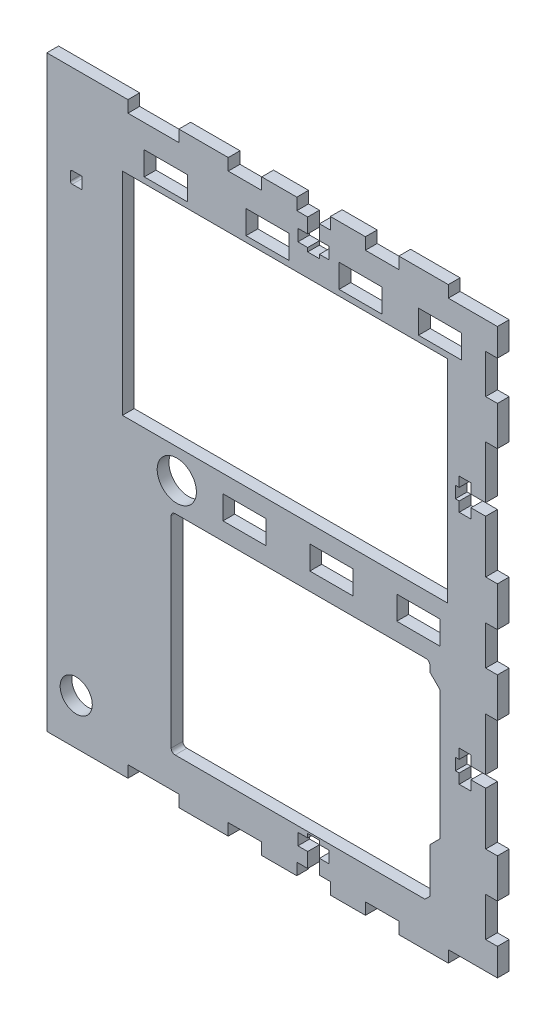
SolidWorks part; units mm, degrees
material "Balsa"
ref_plane "Alzado" through (0, 0, 0) normal (0, 0, 1) x (1, 0, 0)
ref_plane "Planta" through (0, 0, 0) normal (0, 1, 0) x (1, 0, 0)
ref_plane "Vista lateral" through (0, 0, 0) normal (1, 0, 0) x (0, 0, -1)
sketch "Croquis1" plane through (0, 0, 0) normal (0, 0, 1) x (1, 0, 0)
  line L0 (-0.0001, 147) -> (-0.0001, 1.377)
  line L1 (99.9999, 2.9999) -> (99.9999, 9.9999)
  line L2 (99.9999, 9.9999) -> (96.9999, 9.9999)
  line L3 (96.9999, 9.9999) -> (96.9999, 19.9999)
  line L4 (96.9999, 19.9999) -> (99.9999, 19.9999)
  line L5 (99.9999, 19.9999) -> (99.9999, 29.9999)
  line L6 (99.9999, 69.9999) -> (96.9999, 69.9999)
  line L7 (96.9999, 69.9999) -> (96.9999, 79.9999)
  line L8 (96.9999, 79.9999) -> (99.9999, 79.9999)
  line L9 (99.9999, 119.9999) -> (99.9999, 129.9999)
  line L10 (99.9999, 129.9999) -> (96.9999, 129.9999)
  line L11 (96.9999, 129.9999) -> (96.9999, 139.9999)
  line L12 (96.9999, 139.9999) -> (99.9999, 139.9999)
  line L13 (99.9999, 147) -> (99.9999, 139.9999)
  line L14 (96.9999, 46.4372) -> (96.9999, 59.8749)
  line L15 (96.9999, 106.5622) -> (96.9999, 119.9999)
  line L17 (63.1318, 69.011) -> (52.1318, 69.011)
  line L22 (4.2999, 79.511) -> (87.2999, 79.511)
  line L23 (87.2999, 79.511) -> (87.2999, 133.511)
  line L24 (87.2999, 133.511) -> (4.2999, 133.511)
  line L25 (4.2999, 133.511) -> (4.2999, 79.511)
  line L26 (82.7746, 61.971) -> (82.7746, 63.495)
  line L27 (81.7586, 64.511) -> (17.7506, 64.511)
  line L28 (16.7346, 63.495) -> (16.7346, 12.187)
  line L29 (17.7506, 11.171) -> (81.5046, 11.171)
  line L30 (81.5046, 11.171) -> (82.7746, 12.441)
  line L31 (82.7746, 12.441) -> (82.7746, 23.871)
  line L32 (82.7746, 23.871) -> (85.3146, 26.411)
  line L33 (85.3146, 26.411) -> (85.3146, 59.431)
  line L34 (85.3146, 59.431) -> (82.7746, 61.971)
  line L35 (63.1318, 69.011) -> (63.1318, 75.011)
  line L36 (63.1318, 75.011) -> (52.1318, 75.011)
  line L37 (52.1318, 69.011) -> (52.1318, 75.011)
  line L38 (40.9518, 69.011) -> (29.9518, 69.011)
  line L39 (40.9518, 69.011) -> (40.9518, 75.011)
  line L40 (40.9518, 75.011) -> (29.9518, 75.011)
  line L41 (29.9518, 69.011) -> (29.9518, 75.011)
  line L99 (52.1318, 71.811) -> (52.1318, 69.011)
  line L100 (52.1318, 69.011) -> (57.4318, 69.011)
  line L101 (57.8318, 69.011) -> (63.1318, 69.011)
  line L102 (63.1318, 69.011) -> (63.1318, 71.811)
  line L103 (63.1318, 72.211) -> (63.1318, 75.011)
  line L104 (63.1318, 75.011) -> (57.4318, 75.011)
  line L105 (57.4318, 75.011) -> (52.1318, 75.011)
  line L106 (52.1318, 75.011) -> (52.1318, 72.211)
  line L107 (74.3146, 72.211) -> (74.3146, 69.011)
  line L108 (74.3146, 69.011) -> (79.6146, 69.011)
  line L109 (79.6146, 69.011) -> (85.3146, 69.011)
  line L110 (85.3146, 69.011) -> (85.3146, 72.211)
  line L111 (85.3146, 72.211) -> (85.3146, 75.011)
  line L112 (85.3146, 75.011) -> (79.6146, 75.011)
  line L113 (79.6146, 75.011) -> (74.3146, 75.011)
  line L114 (74.3146, 75.011) -> (74.3146, 72.211)
  line L115 (29.9518, 71.811) -> (29.9518, 69.011)
  line L116 (29.9518, 69.011) -> (35.2518, 69.011)
  line L117 (35.6518, 69.011) -> (40.9518, 69.011)
  line L118 (40.9518, 69.011) -> (40.9518, 71.811)
  line L119 (40.9518, 72.211) -> (40.9518, 75.011)
  line L120 (40.9518, 75.011) -> (35.6518, 75.011)
  line L121 (35.2518, 75.011) -> (29.9518, 75.011)
  line L122 (29.9518, 75.011) -> (29.9518, 72.211)
  line L123 (9.8589, 138.1999) -> (9.8589, 134.9999)
  line L124 (9.8589, 134.9999) -> (15.1589, 134.9999)
  line L125 (15.1589, 134.9999) -> (20.8589, 134.9999)
  line L126 (20.8589, 134.9999) -> (20.8589, 138.1999)
  line L127 (20.8589, 138.1999) -> (20.8589, 140.9999)
  line L128 (20.8589, 140.9999) -> (15.5589, 140.9999)
  line L129 (15.5589, 140.9999) -> (9.8589, 140.9999)
  line L130 (9.8589, 140.9999) -> (9.8589, 138.1999)
  line L131 (35.8422, 138.1999) -> (35.8422, 134.9999)
  line L132 (35.8422, 134.9999) -> (41.5422, 134.9999)
  line L133 (41.5422, 134.9999) -> (46.8422, 134.9999)
  line L134 (46.8422, 134.9999) -> (46.8422, 138.1999)
  line L135 (46.8422, 138.1999) -> (46.8422, 140.9999)
  line L136 (46.8422, 140.9999) -> (41.1422, 140.9999)
  line L137 (41.1422, 140.9999) -> (35.8422, 140.9999)
  line L138 (35.8422, 140.9999) -> (35.8422, 138.1999)
  line L139 (59.5749, 138.1999) -> (59.5749, 134.9999)
  line L140 (59.5749, 134.9999) -> (64.8749, 134.9999)
  line L141 (64.8749, 134.9999) -> (70.5749, 134.9999)
  line L142 (70.5749, 134.9999) -> (70.5749, 138.1999)
  line L143 (70.5749, 138.1999) -> (70.5749, 140.9999)
  line L144 (70.5749, 140.9999) -> (64.8749, 140.9999)
  line L145 (64.8749, 140.9999) -> (59.5749, 140.9999)
  line L146 (59.5749, 140.9999) -> (59.5749, 138.1999)
  line L147 (79.8589, 138.1999) -> (79.8589, 134.9999)
  line L148 (79.8589, 134.9999) -> (85.1589, 134.9999)
  line L149 (85.1589, 134.9999) -> (90.8589, 134.9999)
  line L150 (90.8589, 134.9999) -> (90.8589, 138.1999)
  line L151 (90.8589, 138.1999) -> (90.8589, 140.9999)
  line L152 (90.8589, 140.9999) -> (85.1589, 140.9999)
  line L153 (85.1589, 140.9999) -> (79.8589, 140.9999)
  line L154 (79.8589, 140.9999) -> (79.8589, 138.1999)
  line L155 (93.2502, 106.5622) -> (96.9999, 106.5622)
  line L156 (90.2499, 109.0626) -> (93.2502, 109.0626)
  line L157 (90.2499, 103.5622) -> (90.2499, 101.0622)
  line L158 (90.2499, 101.0622) -> (93.2502, 101.0622)
  line L159 (93.2502, 106.5622) -> (93.2502, 109.0626)
  line L160 (90.2499, 106.5622) -> (90.2499, 109.0626)
  line L161 (89.2749, 106.5622) -> (90.2499, 106.5622)
  line L162 (93.2502, 103.5622) -> (93.2502, 101.0622)
  line L163 (89.2749, 103.5622) -> (90.2499, 103.5622)
  line L164 (96.9999, 103.5622) -> (93.2502, 103.5622)
  line L165 (93.2502, 46.4372) -> (96.9999, 46.4372)
  line L166 (90.2499, 48.9376) -> (93.2502, 48.9376)
  line L167 (90.2499, 43.4372) -> (90.2499, 40.9372)
  line L168 (90.2499, 40.9372) -> (93.2502, 40.9372)
  line L169 (93.2502, 46.4372) -> (93.2502, 48.9376)
  line L170 (90.2499, 46.4372) -> (90.2499, 48.9376)
  line L171 (89.2749, 46.4372) -> (90.2499, 46.4372)
  line L172 (93.2502, 43.4372) -> (93.2502, 40.9372)
  line L173 (89.2749, 43.4372) -> (90.2499, 43.4372)
  line L174 (96.9999, 43.4372) -> (93.2502, 43.4372)
  line L175 (96.9999, 29.9999) -> (96.9999, 43.4372)
  line L176 (96.9999, 90.1249) -> (96.9999, 103.5622)
  line L177 (96.9999, 59.8749) -> (99.9999, 59.8749)
  line L178 (96.9999, 29.9999) -> (99.9999, 29.9999)
  line L179 (96.9999, 90.1249) -> (99.9999, 90.1249)
  line L180 (96.9999, 119.9999) -> (99.9999, 119.9999)
  line L181 (29.9518, 72.211) -> (29.9518, 71.811)
  line L182 (51.5795, 6.7497) -> (51.5795, 3.0001)
  line L183 (49.0791, 9.7501) -> (49.0791, 6.7497)
  line L184 (54.5795, 9.7501) -> (57.0795, 9.7501)
  line L185 (57.0795, 9.7501) -> (57.0795, 6.7497)
  line L186 (51.5795, 6.7497) -> (49.0791, 6.7497)
  line L187 (51.5795, 9.7501) -> (49.0791, 9.7501)
  line L188 (51.5795, 10.7251) -> (51.5795, 9.7501)
  line L189 (54.5795, 6.7497) -> (57.0795, 6.7497)
  line L190 (54.5795, 10.7251) -> (54.5795, 9.7501)
  line L191 (54.5795, 3.0001) -> (54.5795, 6.7497)
  line L192 (87.4612, 3.0001) -> (87.4612, 0.0001)
  line L193 (66.3092, 3.0001) -> (66.3092, 0.0001)
  line L194 (74.8405, 0.0001) -> (74.8405, 3.0001)
  line L195 (74.8405, 3.0001) -> (66.3092, 3.0001)
  line L196 (74.8405, 0.0001) -> (87.4612, 0.0001)
  line L197 (66.3092, 0.0001) -> (57.3592, 0.0001)
  line L198 (57.3592, 0.0001) -> (57.3592, 3.0001)
  line L199 (48.8999, 3.0001) -> (48.7999, 3.0001)
  line L200 (57.3592, 3.0001) -> (54.5795, 3.0001)
  line L201 (48.7999, 3.0001) -> (48.7999, 0.0001)
  line L202 (48.7999, 0.0001) -> (39.8499, 0.0001)
  line L203 (39.8499, 0.0001) -> (39.8499, 3)
  line L204 (39.8499, 3) -> (31.2999, 3)
  line L205 (31.2999, 3) -> (31.2999, 0)
  line L206 (18.6999, 0) -> (31.2999, 0)
  line L207 (18.6999, 0) -> (18.6999, 3)
  line L208 (18.6999, 3) -> (-0.0001, 3)
  line L209 (51.5795, 10.7251) -> (54.5795, 10.7251)
  line L210 (87.4612, 3.0001) -> (99.9999, 3.0001)
  line L211 (51.5795, 143.2503) -> (51.5795, 146.9999)
  line L212 (49.0791, 140.2499) -> (49.0791, 143.2503)
  line L213 (54.5795, 140.2499) -> (57.0795, 140.2499)
  line L214 (57.0795, 140.2499) -> (57.0795, 143.2503)
  line L215 (51.5795, 143.2503) -> (49.0791, 143.2503)
  line L216 (51.5795, 140.2499) -> (49.0791, 140.2499)
  line L217 (51.5795, 139.2749) -> (51.5795, 140.2499)
  line L218 (54.5795, 143.2503) -> (57.0795, 143.2503)
  line L219 (54.5795, 139.2749) -> (54.5795, 140.2499)
  line L220 (54.5795, 146.9999) -> (54.5795, 143.2503)
  line L221 (99.9999, 146.9999) -> (87.4612, 146.9999)
  line L222 (87.4612, 146.9999) -> (87.4612, 149.9999)
  line L223 (66.3092, 146.9999) -> (66.3092, 149.9999)
  line L224 (74.8405, 149.9999) -> (74.8405, 146.9999)
  line L225 (74.8405, 146.9999) -> (66.3092, 146.9999)
  line L226 (74.8405, 149.9999) -> (87.4612, 149.9999)
  line L227 (66.3092, 149.9999) -> (57.3592, 149.9999)
  line L228 (57.3592, 149.9999) -> (57.3592, 146.9999)
  line L230 (57.3592, 146.9999) -> (54.5795, 146.9999)
  line L231 (48.7999, 146.9999) -> (48.7999, 149.9999)
  line L232 (48.7999, 149.9999) -> (39.8499, 149.9999)
  line L233 (39.8499, 149.9999) -> (39.8499, 147)
  line L234 (39.8499, 147) -> (31.2999, 147)
  line L235 (31.2999, 147) -> (31.2999, 150)
  line L236 (18.6999, 150) -> (31.2999, 150)
  line L237 (18.6999, 150) -> (18.6999, 147)
  line L238 (18.6999, 147) -> (-0.0001, 147)
  line L239 (51.5795, 139.2749) -> (54.5795, 139.2749)
  line L240 (89.2749, 46.4372) -> (89.2749, 43.4372)
  line L241 (89.2749, 106.5622) -> (89.2749, 103.5622)
  line L242 (99.9999, 79.9999) -> (99.9999, 90.1249)
  line L243 (99.9999, 59.8749) -> (99.9999, 69.9999)
  line L244 (51.5795, 146.9999) -> (48.7999, 146.9999)
  line L245 (51.5795, 3.0001) -> (48.7999, 3.0001)
  circle A0 centre (18.1678, 72.011) radius 5
  circle A1 centre (7.4999, 10.9999) radius 4.1
  arc A2 (8.9999, 14.8156) -> (4.9451, 7.7932) centre (7.4999, 10.9999) ccw
  arc A3 (5.9999, 7.1841) -> (10.0544, 14.2068) centre (7.4999, 10.9999) ccw
  arc A4 (82.7746, 63.495) -> (81.7586, 64.511) centre (81.7586, 63.495) ccw
  arc A5 (17.7506, 64.511) -> (16.7346, 63.495) centre (17.7506, 63.495) ccw
  arc A6 (16.7346, 12.187) -> (17.7506, 11.171) centre (17.7506, 12.187) ccw
  circle A19 centre (57.6318, 72.011) radius 0.4
  circle A20 centre (79.8146, 72.011) radius 0.4
  arc A21 (13.1718, 71.811) -> (17.9678, 67.015) centre (18.1678, 72.011) ccw
  arc A22 (18.3678, 67.015) -> (23.1638, 71.811) centre (18.1678, 72.011) ccw
  arc A23 (23.1638, 72.211) -> (18.3678, 77.007) centre (18.1678, 72.011) ccw
  arc A24 (17.9678, 77.007) -> (13.1718, 72.211) centre (18.1678, 72.011) ccw
  circle A25 centre (35.4518, 72.011) radius 0.4
  circle A26 centre (15.3589, 137.9999) radius 0.4
  circle A27 centre (41.3422, 137.9999) radius 0.4
  circle A28 centre (65.0749, 137.9999) radius 0.4
  circle A29 centre (85.3589, 137.9999) radius 0.4
extrude "Saliente-Extruir1" add sketch "Croquis1" along normal mid plane 3 contours L245 L182 L186 L183 L187 L188 L209 L190 L184 L185 L189 L191 L200 L198 L197 L193 L195 L194 L196 L192 L210 L1 L2 L3 L4 L5 L178 L175 L174 L172 L168 L167 L173 L240 L171 L170 L166 L169 L165 L14 L177 L243 L6 L7 L8 L242 L179 L176 L164 L162 L158 | A1
sketch "Croquis2" plane through (0, 0, 1.5) normal (0, 0, 1) x (1, 0, 0)
  line L0 (-0.0001, 75) -> (96.9999, 74.9999) construction
  line L1 (-0.0001, 147) -> (-0.0001, 3) construction
  line L2 (96.9999, 69.9999) -> (96.9999, 79.9999) construction
sketch "Croquis3" plane through (-0.0001, 0, 0) normal (-1, 0, 0) x (0, 0, 1)
  line L4 (-1.5, 147) -> (-1.5, 3)
  line L5 (-1.5, 3) -> (1.5, 3)
  line L6 (1.5, 3) -> (1.5, 147)
  line L7 (1.5, 147) -> (-1.5, 147)
  line L8 (-1.5, 147) -> (-1.5, 3)
  line L9 (-1.5, 3) -> (1.5, 3)
  line L10 (1.5, 3) -> (1.5, 147)
  line L11 (1.5, 147) -> (-1.5, 147)
  dimension "D1" = 0
extrude "Saliente-Extruir2" add sketch "Croquis3" along normal blind 15
sketch "Croquis4" plane through (0, 0, 1.5) normal (0, 0, 1) x (1, 0, 0)
  line L1 (-6, 127.2) -> (-8.5, 127.2)
  line L2 (-6, 127.2) -> (-6, 124.2)
  line L3 (-6, 124.2) -> (-8.5, 124.2)
  line L4 (-9, 126.7) -> (-9, 124.7)
  circle A0 centre (-7.5, 11.7) radius 4.1
  arc A1 (-9, 124.7) -> (-8.5, 124.2) centre (-8.5, 124.7) ccw
  arc A2 (-9, 126.7) -> (-8.5, 127.2) centre (-8.5, 126.7) cw
  point P10 (-9, 124.2)
  dimension "D1" = 8.2
  dimension "D3" = 0.5
  dimension "D2" = 3
extrude "Cortar-Extruir1" cut sketch "Croquis4" against normal blind 23
sketch "Croquis5" plane through (0, 3, 0) normal (0, -1, 0) x (1, 0, 0)
  line L0 (18.6999, -1.5) -> (-15.0001, -1.5) construction
  line L1 (5.6999, -1.5) -> (-4.3001, -1.5)
  line L2 (5.6999, -1.5) -> (5.6999, 1.5)
  line L3 (5.6999, 1.5) -> (-4.3001, 1.5)
  line L4 (-4.3001, -1.5) -> (-4.3001, 1.5)
  line L5 (18.6999, 1.5) -> (-15.0001, 1.5) construction
  line L6 (18.6999, 1.5) -> (18.6999, -1.5) construction
  dimension "D1" = 13
  dimension "D2" = 10
sketch "Croquis7" plane through (0, 3, 0) normal (0, -1, 0) x (1, 0, 0)
  line L0 (18.6999, -1.5) -> (-15.0001, -1.5) construction
  line L1 (6.5, -1.5) -> (-8.5, -1.5)
  line L2 (6.5, -1.5) -> (6.5, 1.5)
  line L3 (6.5, 1.5) -> (-8.5, 1.5)
  line L4 (-8.5, -1.5) -> (-8.5, 1.5)
  dimension "D1" = 15
sketch "Croquis8" plane through (0, 3, 0) normal (0, -1, 0) x (1, 0, 0)
  line L0 (18.6999, -1.5) -> (-15.0001, -1.5) construction
  line L1 (5.6999, -1.5) -> (-15.0001, -1.5)
  line L2 (5.6999, -1.5) -> (5.6999, 1.5)
  line L3 (5.6999, 1.5) -> (-15.0001, 1.5)
  line L4 (-15.0001, -1.5) -> (-15.0001, 1.5)
  line L5 (18.6999, 1.5) -> (-15.0001, 1.5) construction
  line L6 (18.6999, 1.5) -> (18.6999, -1.5) construction
  dimension "D1" = 13
extrude "Saliente-Extruir4" add sketch "Croquis8" along normal blind 3
sketch "Croquis9" plane through (0, 147, 0) normal (0, 1, 0) x (1, 0, 0)
  line L0 (18.6999, -1.5) -> (-15.0001, -1.5) construction
  line L1 (5.6999, -1.5) -> (-15.0001, -1.5)
  line L2 (5.6999, -1.5) -> (5.6999, 1.5)
  line L3 (5.6999, 1.5) -> (-15.0001, 1.5)
  line L4 (-15.0001, -1.5) -> (-15.0001, 1.5)
  line L5 (18.6999, 1.5) -> (-15.0001, 1.5) construction
  line L6 (18.6999, -1.5) -> (18.6999, 1.5) construction
  line L7 (-15.0001, -1.5) -> (-15.0001, 1.5) construction
  dimension "D1" = 13
extrude "Saliente-Extruir5" add sketch "Croquis9" along normal blind 3
